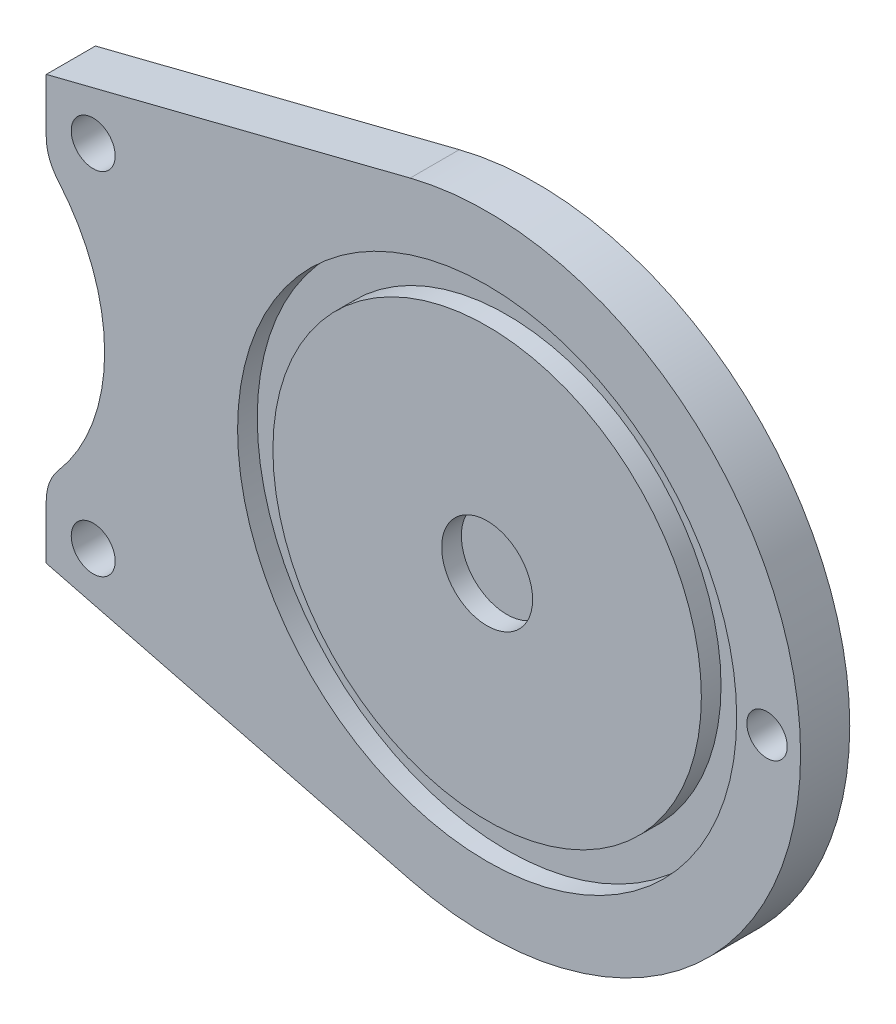
SolidWorks part; units mm, degrees
ref_plane "前视基准面" through (0, 0, 0) normal (0, 0, 1) x (1, 0, 0)
ref_plane "上视基准面" through (0, 0, 0) normal (0, 1, 0) x (1, 0, 0)
ref_plane "右视基准面" through (0, 0, 0) normal (1, 0, 0) x (0, 0, -1)
other "Configuration Table"
sketch "草图1" plane through (0, 0, 0) normal (0, 0, 1) x (1, 0, 0)
  line L0 (-15.6521, 61.7906) -> (-89.6578, 43.0443)
  line L1 (0, 0) -> (-116.9551, 0) construction
  line L2 (-89.6578, 43.0443) -> (-89.6578, 32.0442)
  line L3 (-15.6521, -61.7906) -> (-89.6578, -43.0443)
  line L4 (-107.5479, 0) -> (-115.7938, 0) construction
  line L5 (-89.6578, -32.0442) -> (-89.6578, -43.0443)
  circle A0 centre (0, 0) radius 63.7422
  arc A1 (-87.2428, -25.5275) -> (-87.2428, 25.5275) centre (-116.9551, 0) ccw
  arc A2 (-87.2428, 25.5275) -> (-89.6578, 32.0442) centre (-79.6578, 32.0442) cw
  arc A3 (-87.2428, -25.5275) -> (-89.6578, -32.0442) centre (-79.6578, -32.0442) ccw
  point P7 (-88.075, 0)
  point P17 (-89.6578, -28.0951)
  point P18 (-89.6578, 43.0443)
  point P19 (0, 0)
  point P20 (0, 0)
  point P21 (0, 0)
  dimension "D1" = 10
extrude "凸台-拉伸1" add sketch "草图1" along normal blind 10 contours A1 A3 L5 L3 A0 L0 L2 A2 | A0 L0
sketch "草图2" plane through (0, 0, 10) normal (0, 0, 1) x (1, 0, 0)
  line L0 (0, 0) -> (-80.1077, 0) construction
  circle A0 centre (-80.1077, 35.6771) radius 4.4689
  circle A1 centre (-80.1077, -35.6771) radius 4.4689
  circle A2 centre (56.9197, 0) radius 4.109
extrude "切除-拉伸1" cut sketch "草图2" against normal through all
sketch "草图3" plane through (0, 0, 10) normal (0, 0, 1) x (1, 0, 0)
  circle A0 centre (0, 0) radius 50.7472
  circle A1 centre (0, 0) radius 43.5655
extrude "切除-拉伸3" cut sketch "草图3" against normal blind 4 contours A0 A1
sketch "草图4" plane through (0, 0, 10) normal (0, 0, 1) x (1, 0, 0)
  circle A0 centre (0, 0) radius 9.2449
extrude "切除-拉伸4" cut sketch "草图4" against normal blind 4
sketch "草图5" plane through (0, 0, 0) normal (0, 0, -1) x (-1, 0, 0)
  circle A0 centre (0, 0) radius 18.2013
extrude "切除-拉伸5" cut sketch "草图5" against normal blind 5
